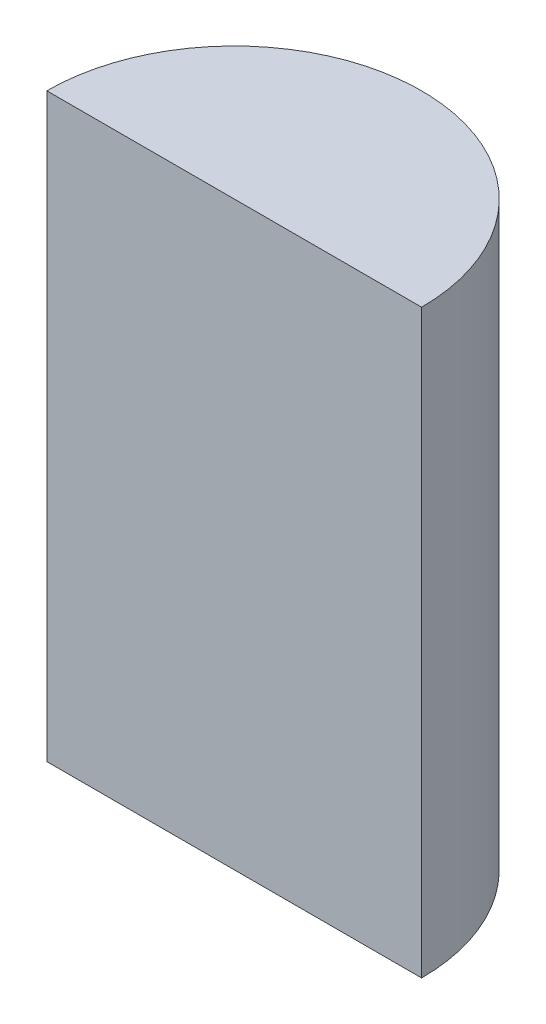
SolidWorks part; units mm, degrees
ref_plane "Front Plane" through (0, 0, 0) normal (0, 0, 1) x (1, 0, 0)
ref_plane "Top Plane" through (0, 0, 0) normal (0, 1, 0) x (1, 0, 0)
ref_plane "Right Plane" through (0, 0, 0) normal (1, 0, 0) x (0, 0, -1)
sketch "Sketch1" plane through (0, 0, 0) normal (0, 1, 0) x (1, 0, 0)
  line L0 (-10, 0) -> (10, 0)
  arc A0 (10, 0) -> (-10, 0) centre (0, 0) ccw
  dimension "D1" = 20
extrude "Boss-Extrude1" add sketch "Sketch1" along normal blind 31
